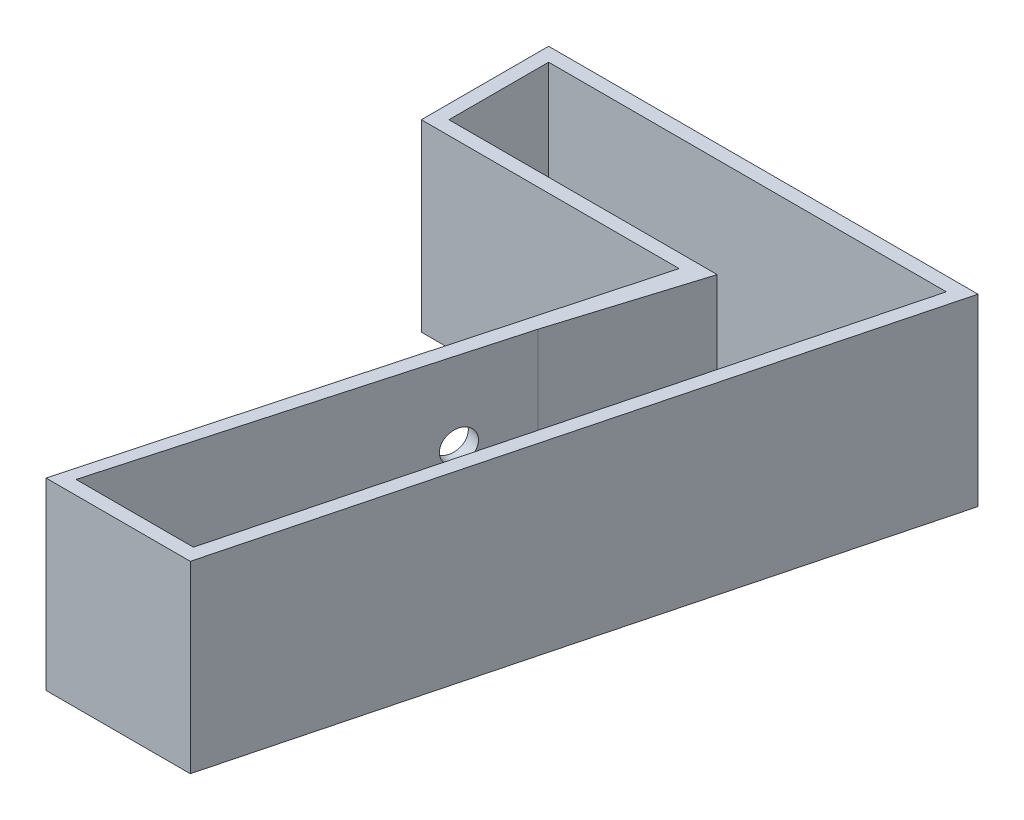
SolidWorks part; units mm, degrees
ref_plane "Front Plane" through (0, 0, 0) normal (0, 0, 1) x (1, 0, 0)
ref_plane "Top Plane" through (0, 0, 0) normal (0, 1, 0) x (1, 0, 0)
ref_plane "Right Plane" through (0, 0, 0) normal (1, 0, 0) x (0, 0, -1)
sketch "Sketch1" plane through (0, 0, 0) normal (0, 1, 0) x (1, 0, 0)
  line L0 (-32.8064, 51.9946) -> (60.5527, 51.9946)
  line L1 (60.5527, 51.9946) -> (25.225, -83.9464)
  line L2 (25.225, -83.9464) -> (-6.1499, -83.9464)
  line L3 (-6.1499, -83.9464) -> (23.25, 24.3237)
  line L4 (23.25, 24.3237) -> (-32.8064, 24.3237)
  line L5 (-32.8064, 24.3237) -> (-32.8064, 51.9946)
  dimension "D1" = 31.375
  dimension "D2" = 140.4564
  dimension "D3" = 93.3592
  dimension "D4" = 112.1908
  dimension "D5" = 56.0564
  dimension "D6" = 27.6708
extrude "Boss-Extrude1" add sketch "Sketch1" along normal blind 40
sketch "Sketch3" plane through (0, 40, 0) normal (0, 1, 0) x (1, 0, 0)
  line L1 (56.1808, 48.9946) -> (56.6735, 48.9946)
  line L2 (56.6735, 48.9946) -> (56.13, 46.9032)
  line L15 (-0.9927, 48.9946) -> (-29.8064, 48.9946)
  line L16 (-29.8064, 48.9946) -> (-29.8064, 27.3237)
  line L17 (-29.8064, 27.3237) -> (28.5177, 27.3237)
  line L18 (28.5177, 27.3237) -> (19.3059, -2.4613)
  line L19 (19.3059, -2.4613) -> (-2.6088, -80.9464)
  line L20 (-2.6088, -80.9464) -> (22.905, -80.9464)
  line L21 (22.905, -80.9464) -> (56.13, 46.9032)
  line L22 (56.1808, 48.9946) -> (-0.9927, 48.9946)
  line L25 (14.2196, 51.9946) -> (14.2196, 48.9946) construction
  line L26 (60.5527, 51.9946) -> (-32.8064, 51.9946) construction
extrude "Cut-Extrude1" cut sketch "Sketch3" against normal through all
sketch "Sketch6" plane through (15.502, 0, 4.2095) normal (-0.9651, 0, -0.2621) x (-0.2621, 0, 0.9651)
  circle A0 centre (11.2462, 22.8012) radius 3.45
  dimension "D1" = 6.9
extrude "Cut-Extrude2" cut sketch "Sketch6" against normal blind 10
sketch "Sketch7" plane through (0, 0, 0) normal (0, 1, 0) x (1, 0, 0)
  circle A0 centre (-17.5986, 46.2308) radius 2.75
  circle A1 centre (45.8858, 18.3851) radius 2.75
  circle A2 centre (7.7587, -54.161) radius 2.75
  point P4 (7.7587, -54.161)
  dimension "D1" = 5.5
  dimension "D2" = 5.5
  dimension "D3" = 5.5
extrude "Boss-Extrude3" add sketch "Sketch7" along normal blind 4.02
sketch "Sketch8" plane through (0, 4.02, 0) normal (0, 1, 0) x (1, 0, 0)
  circle A0 centre (-17.5986, 46.2308) radius 2.225
  circle A1 centre (45.8858, 18.3851) radius 2.225
  circle A2 centre (7.7587, -54.161) radius 2.225
  dimension "D1" = 4.45
  dimension "D2" = 4.45
  dimension "D3" = 4.45
extrude "Cut-Extrude3" cut sketch "Sketch8" against normal through all
